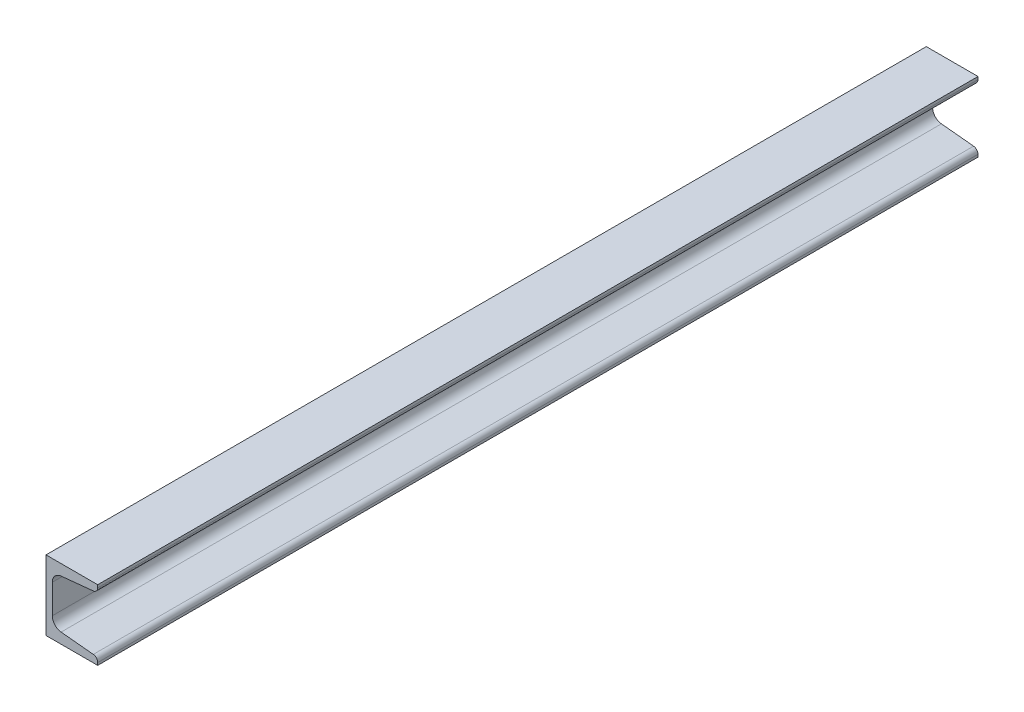
SolidWorks part; units mm, degrees
ref_plane "前视基准面" through (0, 0, 0) normal (0, 0, 1) x (1, 0, 0)
ref_plane "上视基准面" through (0, 0, 0) normal (0, 1, 0) x (1, 0, 0)
ref_plane "右视基准面" through (0, 0, 0) normal (1, 0, 0) x (0, 0, -1)
sketch "草图1" plane through (0, 0, 0) normal (0, 0, 1) x (1, 0, 0)
  line L0 (0, 0) -> (0, 50)
  line L1 (0, 0) -> (37, 0)
  line L2 (-55.9537, 25) -> (55.9537, 25) construction
  line L3 (0, 50) -> (37, 50)
  line L4 (4.5, 14.5099) -> (4.5, 35.2876)
  line L5 (16.25, -10) -> (16.25, 60) construction
  line L6 (10.8035, 7.5447) -> (33.8483, 5.2402)
  line L7 (37, 0) -> (37, 1.7575)
  line L8 (10.8035, 42.2529) -> (33.8483, 44.5574)
  line L9 (37, 48.04) -> (37, 50)
  arc A0 (10.8035, 42.2529) -> (4.5, 35.2876) centre (11.5, 35.2876) ccw
  arc A1 (4.5, 14.5099) -> (10.8035, 7.5447) centre (11.5, 14.5099) ccw
  arc A2 (33.8483, 44.5574) -> (37, 48.04) centre (33.5, 48.04) ccw
  arc A3 (37, 1.7575) -> (33.8483, 5.2402) centre (33.5, 1.7575) ccw
  point P7 (0, 25)
  point P11 (4.5, 25)
  point P14 (16.25, 25)
  point P15 (16.25, 7)
  point P17 (16.25, 43)
  point P19 (16.25, 43)
  point P20 (16.25, 7)
  point P23 (16.25, 43)
  dimension "D5" = 7
  dimension "D6" = 7
  dimension "D7" = 3.5
  dimension "D8" = 3.5
  dimension "h" = 50
  dimension "b" = 37
  dimension "d" = 4.5
  dimension "D1" = 16.25
  dimension "D2" = 7
  dimension "D3" = 5.711
  dimension "D4" = 5.711
extrude "凸台-拉伸1" add sketch "草图1" along normal blind 630
equation "\"高度\"= 50"
equation "\"腿宽\"= 37"
equation "\"腰宽\"= 4.5"
equation "\"h@草图1\"= \"高度\""
equation "\"d@草图1\"= \"腰宽\""
equation "\"D1@草图1\"= ( \"腿宽\" - \"腰宽\" ) / 2"
equation "\"平均腿厚\"= 7"
equation "\"内圆弧半径\"= 7"
equation "\"腿端圆弧半径\"= 3.5"
equation "\"D2@草图1\"= \"平均腿厚\""
equation "\"斜度\"= atn ( 0.1 )"
equation "\"D3@草图1\"= \"斜度\""
equation "\"D4@草图1\"= \"斜度\""
equation "\"D5@草图1\"= \"内圆弧半径\""
equation "\"D6@草图1\"= \"内圆弧半径\""
equation "\"D8@草图1\"= \"腿端圆弧半径\""
equation "\"D7@草图1\"= \"腿端圆弧半径\""
equation "\"b@草图1\"= \"腿宽\""
